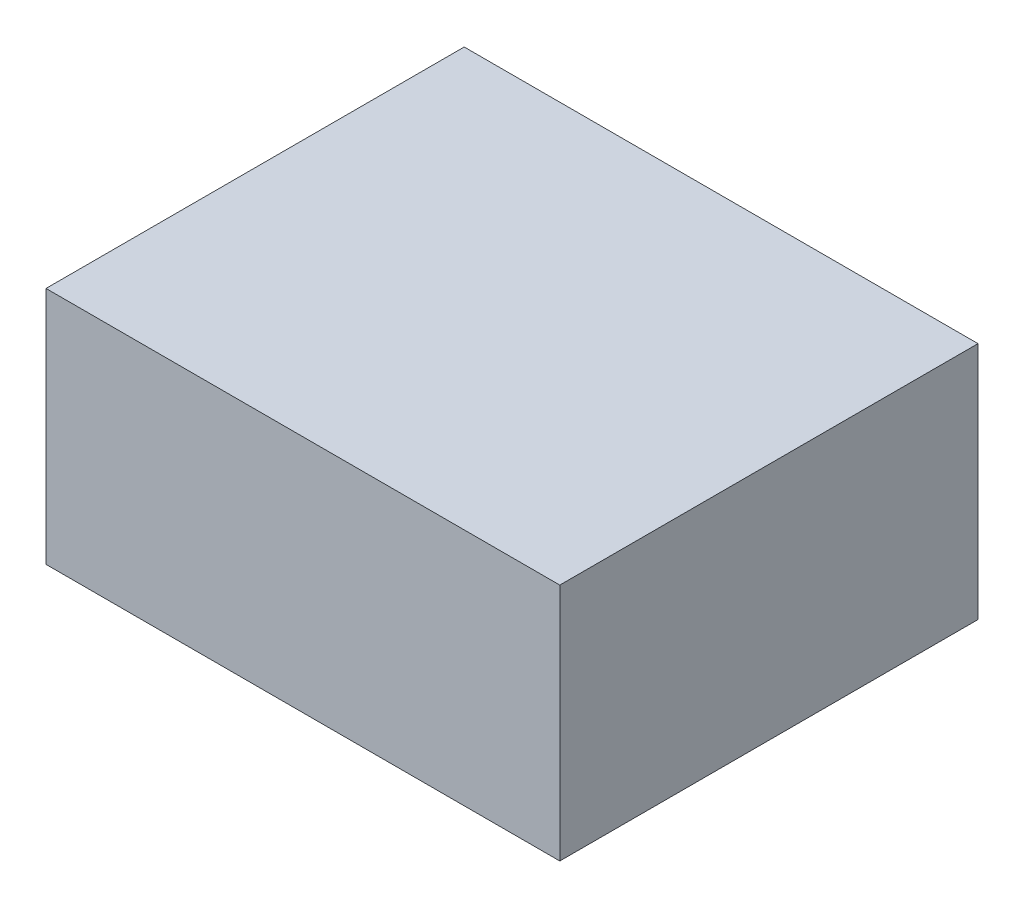
SolidWorks part; units mm, degrees
ref_plane "Front Plane" through (0, 0, 0) normal (0, 0, 1) x (1, 0, 0)
ref_plane "Top Plane" through (0, 0, 0) normal (0, 1, 0) x (1, 0, 0)
ref_plane "Right Plane" through (0, 0, 0) normal (1, 0, 0) x (0, 0, -1)
sketch "Sketch1" plane through (0, 0, 0) normal (0, 1, 0) x (1, 0, 0)
  line L1 (0, 0) -> (43, 0)
  line L2 (0, 0) -> (0, -35)
  line L3 (0, -35) -> (43, -35)
  line L4 (43, 0) -> (43, -35)
  dimension "D1" = 43
  dimension "D2" = 35
extrude "Boss-Extrude2" add sketch "Sketch1" along normal blind 20
sketch "Sketch2" plane through (0, 0, 0) normal (0, 0, 1) x (1, 0, 0)
  line L0 (0, 10) -> (46.1423, 10) construction
  line L1 (0, 20) -> (0, 0) construction
  circle A0 centre (14, 10) radius 2.9
  circle A1 centre (14, 10) radius 1.5
  dimension "D1" = 5.8
  dimension "D3" = 3
  dimension "D2" = 14
